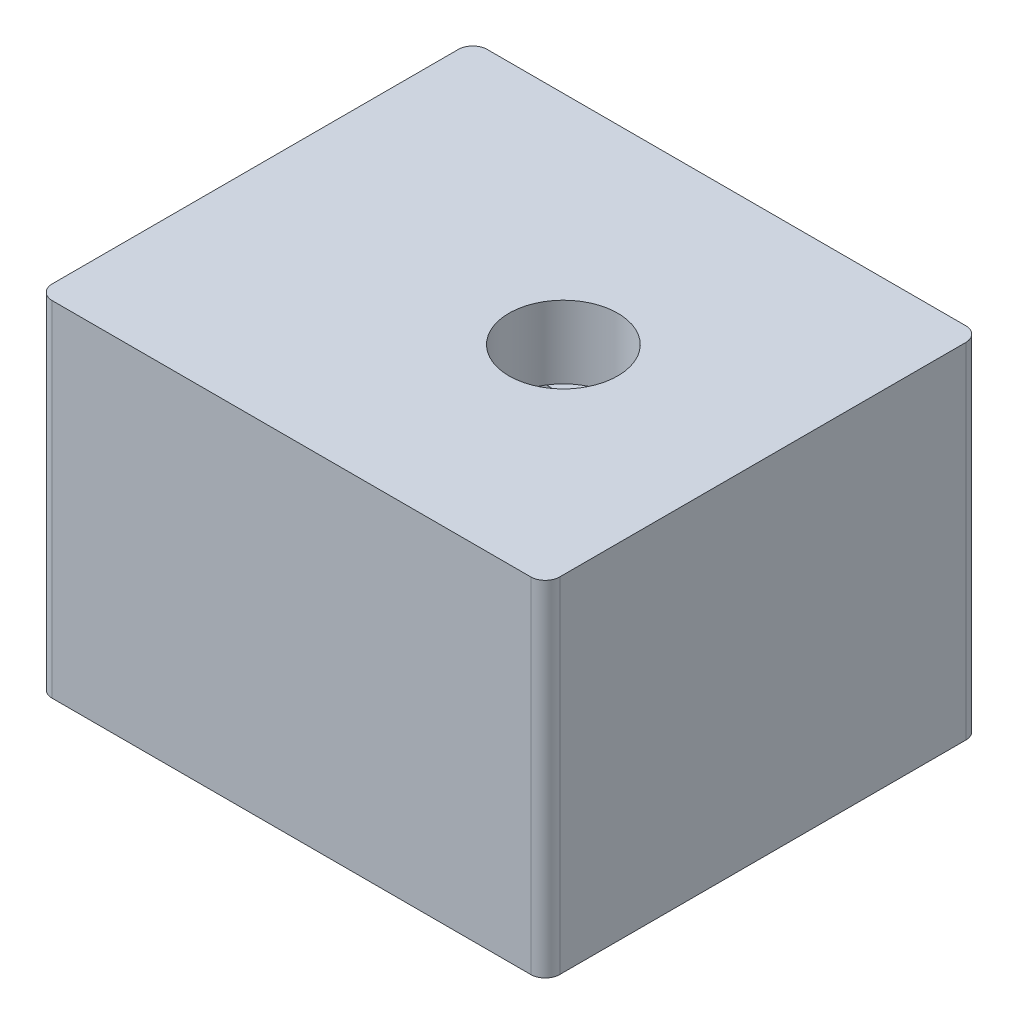
SolidWorks part; units mm, degrees
ref_plane "前视基准面" through (0, 0, 0) normal (0, 0, 1) x (1, 0, 0)
ref_plane "上视基准面" through (0, 0, 0) normal (0, 1, 0) x (1, 0, 0)
ref_plane "右视基准面" through (0, 0, 0) normal (1, 0, 0) x (0, 0, -1)
other "Configuration Table"
sketch "Sketch2" plane through (0, 0, 0) normal (0, 1, 0) x (1, 0, 0)
  line L1 (-70, -60) -> (70, -60)
  line L2 (-70, -60) -> (-70, 60)
  line L3 (-70, 60) -> (70, 60)
  line L4 (70, -60) -> (70, 60)
  point P4 (-70, 0)
  point P6 (0, 60)
  dimension "D1" = 120
  dimension "D2" = 140
extrude "BOX_EXTRUDE" add sketch "Sketch2" along normal blind 90 and the other way blind 5
sketch "Sketch3" plane through (0, 90, 0) normal (0, 1, 0) x (1, 0, 0)
  line L1 (-60, 50) -> (60, 50)
  line L2 (-60, 50) -> (-60, -50)
  line L3 (-60, -50) -> (60, -50)
  line L4 (60, 50) -> (60, -50)
  point P4 (0, 50)
  point P7 (-60, 0)
  dimension "D1" = 120
  dimension "D2" = 100
extrude "BOX_INNER_CUT" cut sketch "Sketch3" against normal blind 50 from offset 20 offset against normal yes
sketch "Sketch6" plane through (0, 90, 0) normal (0, 1, 0) x (1, 0, 0)
  line L0 (0, 30.656) -> (0, -17.5007) construction
  circle A0 centre (15, 0) radius 6
  circle A1 centre (-15, 0) radius 6
  dimension "D2" = 12
  dimension "D1" = 15
extrude "SHAFT_CUT" cut sketch "Sketch6" against normal blind 20 from offset 70 offset against normal yes
sketch "Sketch9" plane through (0, 90, 0) normal (0, 1, 0) x (1, 0, 0)
  circle A0 centre (15, 0) radius 8
  circle A2 centre (-15, 0) radius 16
  dimension "D1" = 16
  dimension "D2" = 32
extrude "BEARING_CUTS_INSIDE_BOX" cut sketch "Sketch9" against normal blind 10 from offset 70 offset against normal yes
sketch "Sketch11" plane through (0, 0, 60) normal (0, 0, 1) x (1, 0, 0)
  line L0 (-70, -5) -> (70, -5) construction
  line L1 (-60, 42) -> (60, 42)
  line L2 (-60, 42) -> (-60, 28)
  line L3 (-60, 28) -> (60, 28)
  line L4 (60, 42) -> (60, 28)
  point P4 (0, 42)
  dimension "D1" = 120
  dimension "D2" = 14
  dimension "D3" = 33
extrude "SCISSOR_CUT" cut sketch "Sketch11" against normal through all from offset 10 offset against normal yes
sketch "Sketch12" plane through (0, 90, 0) normal (0, 1, 0) x (1, 0, 0)
  circle A0 centre (15, 0) radius 15
  dimension "D1" = 30
sketch "Sketch18" plane through (0, 90, 0) normal (0, 1, 0) x (1, 0, 0)
  circle A0 centre (-15, 0) radius 8
  dimension "D1" = 16
extrude "LEFT_BEARING_LID_CUT" cut sketch "Sketch18" against normal blind 10 from offset 10 offset against normal yes
extrude "RIGHT_BEARING_LID_CUT" cut sketch "Sketch12" against normal up to next
fillet "OUTER_EDGES_FILLET" radius 4 4 edges at (-70, 42.5, -60) (70, 42.5, -60) (70, 42.5, 60) (-70, 42.5, 60)
